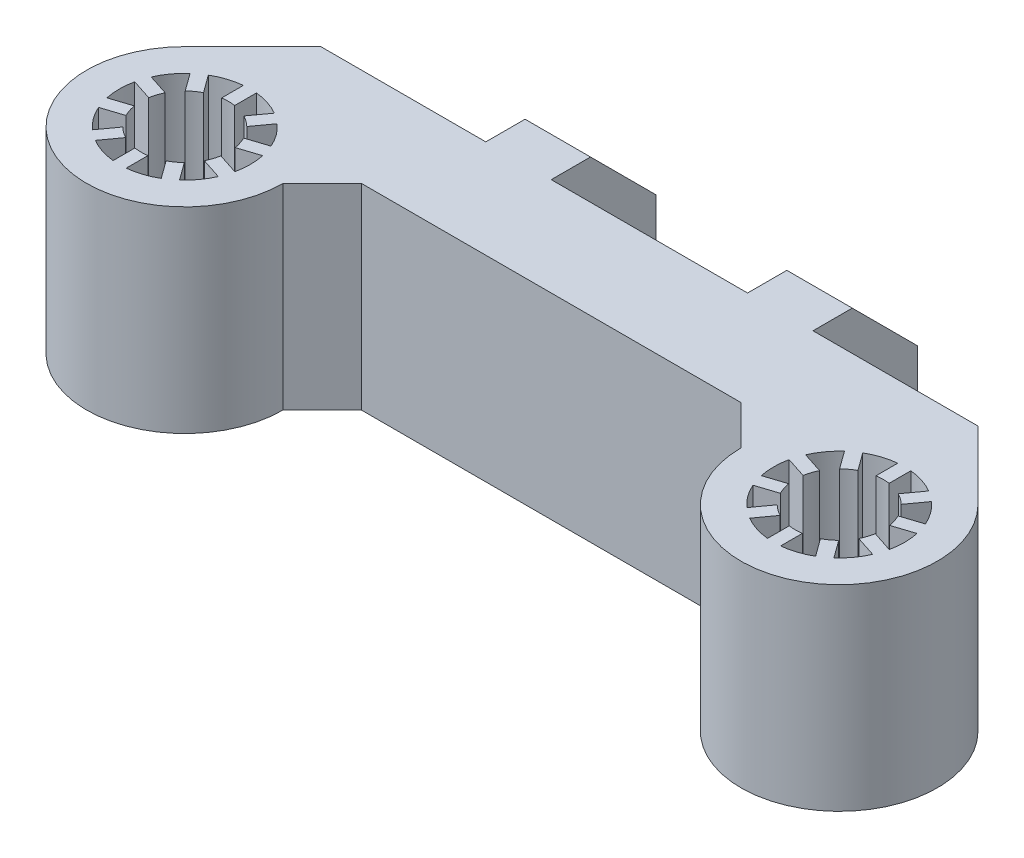
SolidWorks part; units mm, degrees
ref_plane "Front Plane" through (0, 0, 0) normal (0, 0, 1) x (1, 0, 0)
ref_plane "Top Plane" through (0, 0, 0) normal (0, 1, 0) x (1, 0, 0)
ref_plane "Right Plane" through (0, 0, 0) normal (1, 0, 0) x (0, 0, -1)
sketch "Sketch1" plane through (0, 0, 0) normal (0, 1, 0) x (1, 0, 0)
  line L0 (0, 0) -> (0, -14.9433) construction
  line L1 (-25.5, 4.9749) -> (-25.5, 3.3125)
  line L2 (-24.5, 4.9749) -> (-24.5, 3.3125)
  line L3 (-25, 3.35) -> (-25, 5) construction
  line L4 (-21.6713, 3.7309) -> (-22.6485, 2.386)
  line L5 (-22.4803, 4.3187) -> (-23.4575, 2.9737)
  line L6 (-20.114, 1.0618) -> (-21.6951, 0.5481)
  line L7 (-20.4231, 2.0129) -> (-22.0042, 1.4991)
  line L8 (-20.4231, -2.0129) -> (-22.0042, -1.4991)
  line L9 (-20.114, -1.0618) -> (-21.6951, -0.5481)
  line L10 (-22.4803, -4.3187) -> (-23.4575, -2.9737)
  line L11 (-21.6713, -3.7309) -> (-22.6485, -2.386)
  line L12 (-25.5, -4.9749) -> (-25.5, -3.3125)
  line L13 (-24.5, -4.9749) -> (-24.5, -3.3125)
  line L14 (-28.3287, -3.7309) -> (-27.3515, -2.386)
  line L15 (-27.5197, -4.3187) -> (-26.5425, -2.9737)
  line L16 (-29.886, -1.0618) -> (-28.3049, -0.5481)
  line L17 (-29.5769, -2.0129) -> (-27.9958, -1.4991)
  line L18 (-29.5769, 2.0129) -> (-27.9958, 1.4991)
  line L19 (-29.886, 1.0618) -> (-28.3049, 0.5481)
  line L20 (-27.5197, 4.3187) -> (-26.5425, 2.9737)
  line L21 (-28.3287, 3.7309) -> (-27.3515, 2.386)
  line L22 (-30.3033, 5.3033) -> (-25.1066, 10.5)
  line L23 (-25.1066, 10.5) -> (25.1066, 10.5)
  line L24 (0, 10.5) -> (0, 3)
  line L25 (14.5, 3) -> (-14.5, 3)
  line L26 (-14.5, 3) -> (-17.5, 0)
  line L27 (25, 3.35) -> (25, 5) construction
  line L28 (14.5, 3) -> (17.5, 0)
  line L29 (30.3033, 5.3033) -> (25.1066, 10.5)
  line L30 (28.3287, 3.7309) -> (27.3515, 2.386)
  line L31 (27.5197, 4.3187) -> (26.5425, 2.9737)
  line L32 (29.886, 1.0618) -> (28.3049, 0.5481)
  line L33 (29.5769, 2.0129) -> (27.9958, 1.4991)
  line L34 (29.5769, -2.0129) -> (27.9958, -1.4991)
  line L35 (29.886, -1.0618) -> (28.3049, -0.5481)
  line L36 (27.5197, -4.3187) -> (26.5425, -2.9737)
  line L37 (28.3287, -3.7309) -> (27.3515, -2.386)
  line L38 (24.5, -4.9749) -> (24.5, -3.3125)
  line L39 (25.5, -4.9749) -> (25.5, -3.3125)
  line L40 (21.6713, -3.7309) -> (22.6485, -2.386)
  line L41 (22.4803, -4.3187) -> (23.4575, -2.9737)
  line L42 (20.114, -1.0618) -> (21.6951, -0.5481)
  line L43 (20.4231, -2.0129) -> (22.0042, -1.4991)
  line L44 (20.4231, 2.0129) -> (22.0042, 1.4991)
  line L45 (20.114, 1.0618) -> (21.6951, 0.5481)
  line L46 (22.4803, 4.3187) -> (23.4575, 2.9737)
  line L47 (21.6713, 3.7309) -> (22.6485, 2.386)
  line L48 (24.5, 4.9749) -> (24.5, 3.3125)
  line L49 (25.5, 4.9749) -> (25.5, 3.3125)
  line L50 (12.5, 10.5) -> (12.5, 18.5)
  line L51 (-7.5, 10.5) -> (-12.5, 10.5)
  line L52 (-7.5, 10.5) -> (-7.5, 18.5)
  line L53 (-7.5, 18.5) -> (-12.5, 18.5)
  line L54 (-12.5, 10.5) -> (-12.5, 18.5)
  line L55 (7.5, 18.5) -> (12.5, 18.5)
  line L56 (7.5, 10.5) -> (7.5, 18.5)
  circle A0 centre (-25, 0) radius 3.35
  circle A1 centre (-25, 0) radius 7.5
  circle A2 centre (-25, 0) radius 5
  circle A3 centre (25, 0) radius 5
  circle A4 centre (25, 0) radius 7.5
  circle A5 centre (25, 0) radius 3.35
  point P51 (-25, 0)
  dimension "D1" = 6.7
  dimension "D3" = 15
  dimension "D4" = 10
  dimension "D2" = 50
  dimension "D5" = 1
  dimension "D7" = 3
  dimension "D8" = 7.5
  dimension "D9" = 135
  dimension "D10" = 135
  dimension "D11" = 25
  dimension "D12" = 5
  dimension "D13" = 8
  dimension "D6" = 10
extrude "Boss-Extrude1" add sketch "Sketch1" along normal blind 15 contours A1 A2 | L18 A2 L19 A0 | L16 A2 L17 A0 | L14 A2 L15 A0 | L12 A2 L13 A0 | L10 A2 L11 A0 | L8 A2 L9 A0 | L6 A2 L7 A0 | L4 A2 L5 A0 | L2 A2 L1 A0 | L20 A2 L21 A0 | A1 L26 L25 L24 L23 L22 | L54 L23 L52 L53
mirror "Mirror1" about plane through (0, 0, 0) normal (1, 0, 0) of "Boss-Extrude1"
chamfer "Chamfer1" distance 5 angle 45 4 edges at (-10, 0, -18.5) (-10, 15, -18.5) (10, 0, -18.5) (10, 15, -18.5)
sketch "Sketch3" plane through (0, 0, 0) normal (1, 0, 0) x (0, 0, -1)
  line L0 (18.5, 10) -> (18.5, 5) construction
  line L1 (18.5, 7.5) -> (14.5, 7.5) construction
  circle A0 centre (14.5, 7.5) radius 2
  dimension "D1" = 4
  dimension "D2" = 4
extrude "Cut-Extrude1" cut sketch "Sketch3" against normal up to next and the other way up to next
